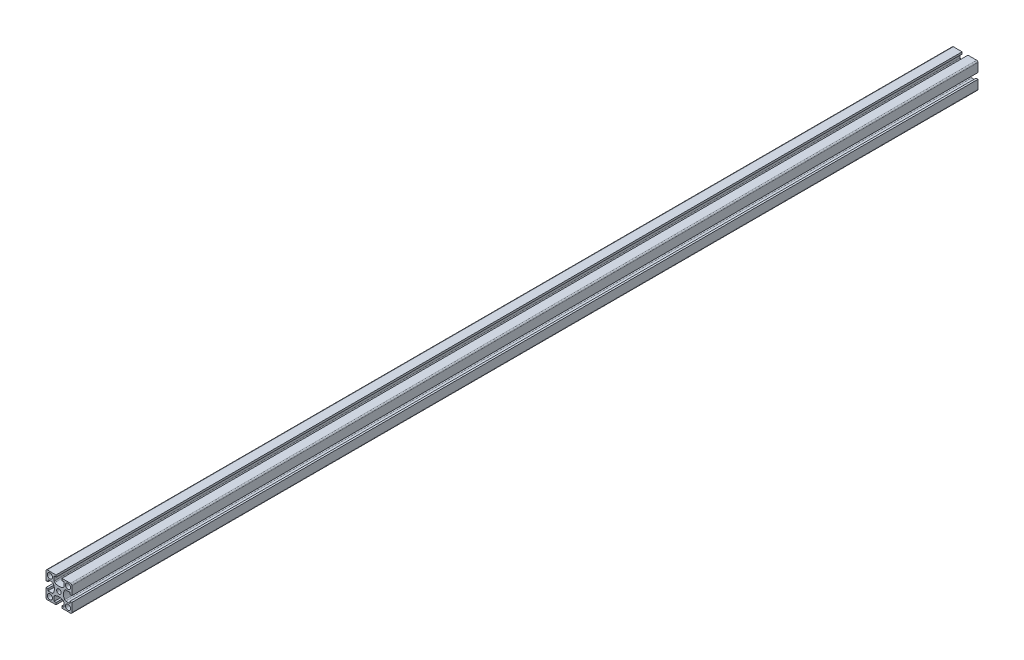
SolidWorks part; units mm, degrees
ref_plane "Front Plane" through (0, 0, 0) normal (0, 0, 1) x (1, 0, 0)
ref_plane "Top Plane" through (0, 0, 0) normal (0, 1, 0) x (1, 0, 0)
ref_plane "Right Plane" through (0, 0, 0) normal (1, 0, 0) x (0, 0, -1)
sketch "Sketch1" plane through (0, 0, 0) normal (0, 0, 1) x (1, 0, 0)
  line L64 (-10, 9) -> (-10, 2.25)
  line L65 (-10, 2.25) -> (-8.5, 2.25)
  line L66 (-8.5, 2.25) -> (-8.5, 3.75)
  line L67 (-8.5, 3.75) -> (-5.2369, 3.75)
  line L68 (-5.2369, -3.75) -> (-8.5, -3.75)
  line L69 (-8.5, -3.75) -> (-8.5, -2.25)
  line L70 (-8.5, -2.25) -> (-10, -2.25)
  line L71 (-10, -2.25) -> (-10, -9)
  line L72 (-9, -10) -> (-2.25, -10)
  line L73 (-2.25, -10) -> (-2.25, -8.5)
  line L74 (-2.25, -8.5) -> (-3.75, -8.5)
  line L75 (-3.75, -8.5) -> (-3.75, -5.2369)
  line L76 (3.75, -5.2369) -> (3.75, -8.5)
  line L77 (3.75, -8.5) -> (2.25, -8.5)
  line L78 (2.25, -8.5) -> (2.25, -10)
  line L79 (2.25, -10) -> (9, -10)
  line L80 (10, -9) -> (10, -2.25)
  line L81 (10, -2.25) -> (8.5, -2.25)
  line L82 (8.5, -2.25) -> (8.5, -3.75)
  line L83 (8.5, -3.75) -> (5.2369, -3.75)
  line L84 (5.2369, 3.75) -> (8.5, 3.75)
  line L85 (8.5, 3.75) -> (8.5, 2.25)
  line L86 (8.5, 2.25) -> (10, 2.25)
  line L87 (10, 2.25) -> (10, 9)
  line L88 (9, 10) -> (2.25, 10)
  line L89 (2.25, 10) -> (2.25, 8.5)
  line L90 (2.25, 8.5) -> (3.75, 8.5)
  line L91 (3.75, 8.5) -> (3.75, 5.2369)
  line L92 (-3.75, 5.2369) -> (-3.75, 8.5)
  line L93 (-3.75, 8.5) -> (-2.25, 8.5)
  line L94 (-2.25, 8.5) -> (-2.25, 10)
  line L95 (-2.25, 10) -> (-9, 10)
  circle A5 centre (-7, -7) radius 2
  circle A6 centre (7, -7) radius 2
  circle A7 centre (7, 7) radius 2
  circle A8 centre (0, 0) radius 1.75
  circle A9 centre (-7, 7) radius 2
  arc A32 (-9, 10) -> (-10, 9) centre (-9, 9) ccw
  arc A33 (-4.3708, 3.25) -> (-5.2369, 3.75) centre (-5.2369, 2.75) ccw
  arc A34 (-4.3708, -3.25) -> (-4.3708, 3.25) centre (-10, 0) ccw
  arc A35 (-5.2369, -3.75) -> (-4.3708, -3.25) centre (-5.2369, -2.75) ccw
  arc A36 (-10, -9) -> (-9, -10) centre (-9, -9) ccw
  arc A37 (-3.25, -4.3708) -> (-3.75, -5.2369) centre (-2.75, -5.2369) ccw
  arc A38 (3.25, -4.3708) -> (-3.25, -4.3708) centre (0, -10) ccw
  arc A39 (3.75, -5.2369) -> (3.25, -4.3708) centre (2.75, -5.2369) ccw
  arc A40 (9, -10) -> (10, -9) centre (9, -9) ccw
  arc A41 (4.3708, -3.25) -> (5.2369, -3.75) centre (5.2369, -2.75) ccw
  arc A42 (4.3708, 3.25) -> (4.3708, -3.25) centre (10, 0) ccw
  arc A43 (5.2369, 3.75) -> (4.3708, 3.25) centre (5.2369, 2.75) ccw
  arc A44 (10, 9) -> (9, 10) centre (9, 9) ccw
  arc A45 (3.25, 4.3708) -> (3.75, 5.2369) centre (2.75, 5.2369) ccw
  arc A46 (-3.25, 4.3708) -> (3.25, 4.3708) centre (0, 10) ccw
  arc A47 (-3.75, 5.2369) -> (-3.25, 4.3708) centre (-2.75, 5.2369) ccw
extrude "Boss-Extrude1" add sketch "Sketch1" along normal blind 700
